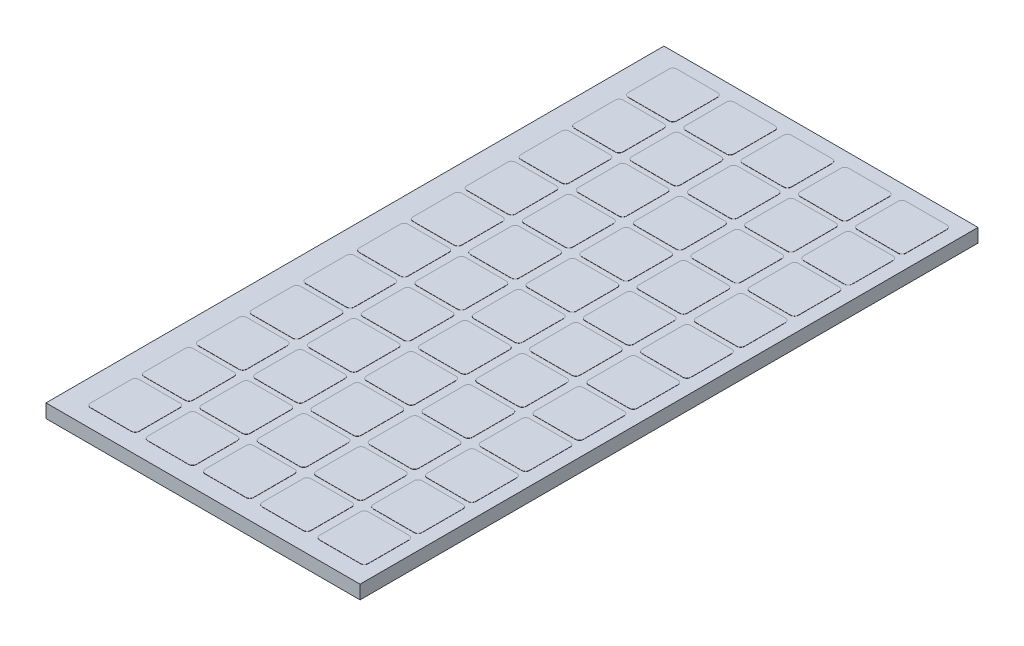
SolidWorks part; units mm, degrees
ref_plane "Спереди" through (0, 0, 0) normal (0, 0, 1) x (1, 0, 0)
ref_plane "Сверху" through (0, 0, 0) normal (0, 1, 0) x (1, 0, 0)
ref_plane "Справа" through (0, 0, 0) normal (1, 0, 0) x (0, 0, -1)
other "Центр тяжести"
other "Configuration Table"
sketch "Эскиз5" plane through (0, 0, 0) normal (0, 1, 0) x (1, 0, 0)
  line L0 (0, 0) -> (0, 1586)
  line L5 (0, 1586) -> (806, 1586)
  line L6 (806, 1586) -> (806, 0)
  line L7 (806, 0) -> (0, 0)
extrude "Бобышка-Вытянуть1" add sketch "Эскиз5" along normal blind 35
sketch "Эскиз7" plane through (0, 35, 0) normal (0, 1, 0) x (1, 0, 0)
  line L0 (806, 1586) -> (0, 1586) construction
  line L1 (761, 1551) -> (656, 1551)
  line L2 (771, 1541) -> (771, 1436)
  line L3 (761, 1426) -> (656, 1426)
  line L4 (646, 1541) -> (646, 1436)
  line L5 (806, 0) -> (806, 1586) construction
  line L6 (771, 1403) -> (771, 1298)
  line L7 (761, 1413) -> (656, 1413)
  line L8 (646, 1403) -> (646, 1298)
  line L9 (761, 1288) -> (656, 1288)
  line L10 (771, 1265) -> (771, 1160)
  line L11 (761, 1275) -> (656, 1275)
  line L12 (646, 1265) -> (646, 1160)
  line L13 (761, 1150) -> (656, 1150)
  line L14 (771, 1127) -> (771, 1022)
  line L15 (761, 1137) -> (656, 1137)
  line L16 (646, 1127) -> (646, 1022)
  line L17 (761, 1012) -> (656, 1012)
  line L18 (771, 989) -> (771, 884)
  line L19 (761, 999) -> (656, 999)
  line L20 (646, 989) -> (646, 884)
  line L21 (761, 874) -> (656, 874)
  line L22 (771, 851) -> (771, 746)
  line L23 (761, 861) -> (656, 861)
  line L24 (646, 851) -> (646, 746)
  line L25 (761, 736) -> (656, 736)
  line L26 (771, 713) -> (771, 608)
  line L27 (761, 723) -> (656, 723)
  line L28 (646, 713) -> (646, 608)
  line L29 (761, 598) -> (656, 598)
  line L30 (771, 575) -> (771, 470)
  line L31 (761, 585) -> (656, 585)
  line L32 (646, 575) -> (646, 470)
  line L33 (761, 460) -> (656, 460)
  line L34 (771, 437) -> (771, 332)
  line L35 (761, 447) -> (656, 447)
  line L36 (646, 437) -> (646, 332)
  line L37 (761, 322) -> (656, 322)
  line L38 (771, 299) -> (771, 194)
  line L39 (761, 309) -> (656, 309)
  line L40 (646, 299) -> (646, 194)
  line L41 (761, 184) -> (656, 184)
  line L42 (771, 161) -> (771, 56)
  line L43 (761, 171) -> (656, 171)
  line L44 (646, 161) -> (646, 56)
  line L45 (761, 46) -> (656, 46)
  line L46 (624, 1541) -> (624, 1436)
  line L47 (614, 1551) -> (509, 1551)
  line L48 (499, 1541) -> (499, 1436)
  line L49 (614, 1426) -> (509, 1426)
  line L50 (624, 1265) -> (624, 1160)
  line L51 (614, 1150) -> (509, 1150)
  line L52 (499, 1265) -> (499, 1160)
  line L53 (614, 1275) -> (509, 1275)
  line L54 (624, 1403) -> (624, 1298)
  line L55 (614, 1288) -> (509, 1288)
  line L56 (499, 1403) -> (499, 1298)
  line L57 (614, 1413) -> (509, 1413)
  line L58 (624, 989) -> (624, 884)
  line L59 (614, 874) -> (509, 874)
  line L60 (499, 989) -> (499, 884)
  line L61 (614, 999) -> (509, 999)
  line L62 (624, 1127) -> (624, 1022)
  line L63 (614, 1012) -> (509, 1012)
  line L64 (499, 1127) -> (499, 1022)
  line L65 (614, 1137) -> (509, 1137)
  line L66 (624, 851) -> (624, 746)
  line L67 (614, 736) -> (509, 736)
  line L68 (499, 851) -> (499, 746)
  line L69 (614, 861) -> (509, 861)
  line L70 (624, 713) -> (624, 608)
  line L71 (614, 598) -> (509, 598)
  line L72 (499, 713) -> (499, 608)
  line L73 (614, 723) -> (509, 723)
  line L74 (624, 575) -> (624, 470)
  line L75 (614, 460) -> (509, 460)
  line L76 (499, 575) -> (499, 470)
  line L77 (614, 585) -> (509, 585)
  line L78 (624, 437) -> (624, 332)
  line L79 (614, 322) -> (509, 322)
  line L80 (499, 437) -> (499, 332)
  line L81 (614, 447) -> (509, 447)
  line L82 (624, 299) -> (624, 194)
  line L83 (614, 184) -> (509, 184)
  line L84 (499, 299) -> (499, 194)
  line L85 (614, 309) -> (509, 309)
  line L86 (624, 161) -> (624, 56)
  line L87 (614, 46) -> (509, 46)
  line L88 (499, 161) -> (499, 56)
  line L89 (614, 171) -> (509, 171)
  line L90 (477, 1541) -> (477, 1436)
  line L91 (467, 1551) -> (362, 1551)
  line L92 (352, 1541) -> (352, 1436)
  line L93 (467, 1426) -> (362, 1426)
  line L94 (477, 1265) -> (477, 1160)
  line L95 (467, 1150) -> (362, 1150)
  line L96 (352, 1265) -> (352, 1160)
  line L97 (467, 1275) -> (362, 1275)
  line L98 (477, 1403) -> (477, 1298)
  line L99 (467, 1288) -> (362, 1288)
  line L100 (352, 1403) -> (352, 1298)
  line L101 (467, 1413) -> (362, 1413)
  line L102 (477, 989) -> (477, 884)
  line L103 (467, 874) -> (362, 874)
  line L104 (352, 989) -> (352, 884)
  line L105 (467, 999) -> (362, 999)
  line L106 (477, 1127) -> (477, 1022)
  line L107 (467, 1012) -> (362, 1012)
  line L108 (352, 1127) -> (352, 1022)
  line L109 (467, 1137) -> (362, 1137)
  line L110 (477, 851) -> (477, 746)
  line L111 (467, 736) -> (362, 736)
  line L112 (352, 851) -> (352, 746)
  line L113 (467, 861) -> (362, 861)
  line L114 (477, 713) -> (477, 608)
  line L115 (467, 598) -> (362, 598)
  line L116 (352, 713) -> (352, 608)
  line L117 (467, 723) -> (362, 723)
  line L118 (477, 575) -> (477, 470)
  line L119 (467, 460) -> (362, 460)
  line L120 (352, 575) -> (352, 470)
  line L121 (467, 585) -> (362, 585)
  line L122 (477, 437) -> (477, 332)
  line L123 (467, 322) -> (362, 322)
  line L124 (352, 437) -> (352, 332)
  line L125 (467, 447) -> (362, 447)
  line L126 (477, 299) -> (477, 194)
  line L127 (467, 184) -> (362, 184)
  line L128 (352, 299) -> (352, 194)
  line L129 (467, 309) -> (362, 309)
  line L130 (477, 161) -> (477, 56)
  line L131 (467, 46) -> (362, 46)
  line L132 (352, 161) -> (352, 56)
  line L133 (467, 171) -> (362, 171)
  line L134 (330, 1541) -> (330, 1436)
  line L135 (320, 1551) -> (215, 1551)
  line L136 (205, 1541) -> (205, 1436)
  line L137 (320, 1426) -> (215, 1426)
  line L138 (330, 1265) -> (330, 1160)
  line L139 (320, 1150) -> (215, 1150)
  line L140 (205, 1265) -> (205, 1160)
  line L141 (320, 1275) -> (215, 1275)
  line L142 (330, 1403) -> (330, 1298)
  line L143 (320, 1288) -> (215, 1288)
  line L144 (205, 1403) -> (205, 1298)
  line L145 (320, 1413) -> (215, 1413)
  line L146 (330, 989) -> (330, 884)
  line L147 (320, 874) -> (215, 874)
  line L148 (205, 989) -> (205, 884)
  line L149 (320, 999) -> (215, 999)
  line L150 (330, 1127) -> (330, 1022)
  line L151 (320, 1012) -> (215, 1012)
  line L152 (205, 1127) -> (205, 1022)
  line L153 (320, 1137) -> (215, 1137)
  line L154 (330, 851) -> (330, 746)
  line L155 (320, 736) -> (215, 736)
  line L156 (205, 851) -> (205, 746)
  line L157 (320, 861) -> (215, 861)
  line L158 (330, 713) -> (330, 608)
  line L159 (320, 598) -> (215, 598)
  line L160 (205, 713) -> (205, 608)
  line L161 (320, 723) -> (215, 723)
  line L162 (330, 575) -> (330, 470)
  line L163 (320, 460) -> (215, 460)
  line L164 (205, 575) -> (205, 470)
  line L165 (320, 585) -> (215, 585)
  line L166 (330, 437) -> (330, 332)
  line L167 (320, 322) -> (215, 322)
  line L168 (205, 437) -> (205, 332)
  line L169 (320, 447) -> (215, 447)
  line L170 (330, 299) -> (330, 194)
  line L171 (320, 184) -> (215, 184)
  line L172 (205, 299) -> (205, 194)
  line L173 (320, 309) -> (215, 309)
  line L174 (330, 161) -> (330, 56)
  line L175 (320, 46) -> (215, 46)
  line L176 (205, 161) -> (205, 56)
  line L177 (320, 171) -> (215, 171)
  line L178 (183, 1541) -> (183, 1436)
  line L179 (173, 1551) -> (68, 1551)
  line L180 (58, 1541) -> (58, 1436)
  line L181 (173, 1426) -> (68, 1426)
  line L182 (183, 1265) -> (183, 1160)
  line L183 (173, 1150) -> (68, 1150)
  line L184 (58, 1265) -> (58, 1160)
  line L185 (173, 1275) -> (68, 1275)
  line L186 (183, 1403) -> (183, 1298)
  line L187 (173, 1288) -> (68, 1288)
  line L188 (58, 1403) -> (58, 1298)
  line L189 (173, 1413) -> (68, 1413)
  line L190 (183, 989) -> (183, 884)
  line L191 (173, 874) -> (68, 874)
  line L192 (58, 989) -> (58, 884)
  line L193 (173, 999) -> (68, 999)
  line L194 (183, 1127) -> (183, 1022)
  line L195 (173, 1012) -> (68, 1012)
  line L196 (58, 1127) -> (58, 1022)
  line L197 (173, 1137) -> (68, 1137)
  line L198 (183, 851) -> (183, 746)
  line L199 (173, 736) -> (68, 736)
  line L200 (58, 851) -> (58, 746)
  line L201 (173, 861) -> (68, 861)
  line L202 (183, 713) -> (183, 608)
  line L203 (173, 598) -> (68, 598)
  line L204 (58, 713) -> (58, 608)
  line L205 (173, 723) -> (68, 723)
  line L206 (183, 575) -> (183, 470)
  line L207 (173, 460) -> (68, 460)
  line L208 (58, 575) -> (58, 470)
  line L209 (173, 585) -> (68, 585)
  line L210 (183, 437) -> (183, 332)
  line L211 (173, 322) -> (68, 322)
  line L212 (58, 437) -> (58, 332)
  line L213 (173, 447) -> (68, 447)
  line L214 (183, 299) -> (183, 194)
  line L215 (173, 184) -> (68, 184)
  line L216 (58, 299) -> (58, 194)
  line L217 (173, 309) -> (68, 309)
  line L218 (183, 161) -> (183, 56)
  line L219 (173, 46) -> (68, 46)
  line L220 (58, 161) -> (58, 56)
  line L221 (173, 171) -> (68, 171)
  arc A0 (173, 1426) -> (183, 1436) centre (173, 1436) ccw
  arc A1 (173, 1551) -> (183, 1541) centre (173, 1541) cw
  arc A2 (68, 1426) -> (58, 1436) centre (68, 1436) cw
  arc A3 (58, 1541) -> (68, 1551) centre (68, 1541) cw
  arc A4 (58, 161) -> (68, 171) centre (68, 161) cw
  arc A5 (183, 56) -> (173, 46) centre (173, 56) cw
  arc A6 (68, 46) -> (58, 56) centre (68, 56) cw
  arc A7 (183, 161) -> (173, 171) centre (173, 161) ccw
  arc A8 (58, 299) -> (68, 309) centre (68, 299) cw
  arc A9 (183, 194) -> (173, 184) centre (173, 194) cw
  arc A10 (68, 184) -> (58, 194) centre (68, 194) cw
  arc A11 (183, 299) -> (173, 309) centre (173, 299) ccw
  arc A12 (58, 437) -> (68, 447) centre (68, 437) cw
  arc A13 (183, 332) -> (173, 322) centre (173, 332) cw
  arc A14 (68, 322) -> (58, 332) centre (68, 332) cw
  arc A15 (183, 437) -> (173, 447) centre (173, 437) ccw
  arc A16 (58, 575) -> (68, 585) centre (68, 575) cw
  arc A17 (183, 470) -> (173, 460) centre (173, 470) cw
  arc A18 (68, 460) -> (58, 470) centre (68, 470) cw
  arc A19 (183, 575) -> (173, 585) centre (173, 575) ccw
  arc A20 (58, 713) -> (68, 723) centre (68, 713) cw
  arc A21 (183, 608) -> (173, 598) centre (173, 608) cw
  arc A22 (68, 598) -> (58, 608) centre (68, 608) cw
  arc A23 (183, 713) -> (173, 723) centre (173, 713) ccw
  arc A24 (58, 851) -> (68, 861) centre (68, 851) cw
  arc A25 (183, 746) -> (173, 736) centre (173, 746) cw
  arc A26 (68, 736) -> (58, 746) centre (68, 746) cw
  arc A27 (183, 851) -> (173, 861) centre (173, 851) ccw
  arc A28 (58, 989) -> (68, 999) centre (68, 989) cw
  arc A29 (183, 884) -> (173, 874) centre (173, 884) cw
  arc A30 (68, 874) -> (58, 884) centre (68, 884) cw
  arc A31 (183, 989) -> (173, 999) centre (173, 989) ccw
  arc A32 (58, 1127) -> (68, 1137) centre (68, 1127) cw
  arc A33 (183, 1022) -> (173, 1012) centre (173, 1022) cw
  arc A34 (68, 1012) -> (58, 1022) centre (68, 1022) cw
  arc A35 (183, 1127) -> (173, 1137) centre (173, 1127) ccw
  arc A36 (58, 1265) -> (68, 1275) centre (68, 1265) cw
  arc A37 (183, 1160) -> (173, 1150) centre (173, 1160) cw
  arc A38 (68, 1150) -> (58, 1160) centre (68, 1160) cw
  arc A39 (183, 1265) -> (173, 1275) centre (173, 1265) ccw
  arc A40 (58, 1403) -> (68, 1413) centre (68, 1403) cw
  arc A41 (183, 1298) -> (173, 1288) centre (173, 1298) cw
  arc A42 (68, 1288) -> (58, 1298) centre (68, 1298) cw
  arc A43 (183, 1403) -> (173, 1413) centre (173, 1403) ccw
  arc A44 (205, 161) -> (215, 171) centre (215, 161) cw
  arc A45 (330, 56) -> (320, 46) centre (320, 56) cw
  arc A46 (215, 46) -> (205, 56) centre (215, 56) cw
  arc A47 (330, 161) -> (320, 171) centre (320, 161) ccw
  arc A48 (205, 299) -> (215, 309) centre (215, 299) cw
  arc A49 (330, 194) -> (320, 184) centre (320, 194) cw
  arc A50 (215, 184) -> (205, 194) centre (215, 194) cw
  arc A51 (330, 299) -> (320, 309) centre (320, 299) ccw
  arc A52 (205, 437) -> (215, 447) centre (215, 437) cw
  arc A53 (330, 332) -> (320, 322) centre (320, 332) cw
  arc A54 (215, 322) -> (205, 332) centre (215, 332) cw
  arc A55 (330, 437) -> (320, 447) centre (320, 437) ccw
  arc A56 (205, 575) -> (215, 585) centre (215, 575) cw
  arc A57 (330, 470) -> (320, 460) centre (320, 470) cw
  arc A58 (215, 460) -> (205, 470) centre (215, 470) cw
  arc A59 (330, 575) -> (320, 585) centre (320, 575) ccw
  arc A60 (205, 713) -> (215, 723) centre (215, 713) cw
  arc A61 (330, 608) -> (320, 598) centre (320, 608) cw
  arc A62 (215, 598) -> (205, 608) centre (215, 608) cw
  arc A63 (330, 713) -> (320, 723) centre (320, 713) ccw
  arc A64 (205, 851) -> (215, 861) centre (215, 851) cw
  arc A65 (330, 746) -> (320, 736) centre (320, 746) cw
  arc A66 (215, 736) -> (205, 746) centre (215, 746) cw
  arc A67 (330, 851) -> (320, 861) centre (320, 851) ccw
  arc A68 (205, 989) -> (215, 999) centre (215, 989) cw
  arc A69 (330, 884) -> (320, 874) centre (320, 884) cw
  arc A70 (215, 874) -> (205, 884) centre (215, 884) cw
  arc A71 (330, 989) -> (320, 999) centre (320, 989) ccw
  arc A72 (205, 1127) -> (215, 1137) centre (215, 1127) cw
  arc A73 (330, 1022) -> (320, 1012) centre (320, 1022) cw
  arc A74 (215, 1012) -> (205, 1022) centre (215, 1022) cw
  arc A75 (330, 1127) -> (320, 1137) centre (320, 1127) ccw
  arc A76 (205, 1265) -> (215, 1275) centre (215, 1265) cw
  arc A77 (330, 1160) -> (320, 1150) centre (320, 1160) cw
  arc A78 (215, 1150) -> (205, 1160) centre (215, 1160) cw
  arc A79 (330, 1265) -> (320, 1275) centre (320, 1265) ccw
  arc A80 (205, 1403) -> (215, 1413) centre (215, 1403) cw
  arc A81 (330, 1298) -> (320, 1288) centre (320, 1298) cw
  arc A82 (215, 1288) -> (205, 1298) centre (215, 1298) cw
  arc A83 (330, 1403) -> (320, 1413) centre (320, 1403) ccw
  arc A84 (215, 1551) -> (205, 1541) centre (215, 1541) ccw
  arc A85 (330, 1436) -> (320, 1426) centre (320, 1436) cw
  arc A86 (205, 1436) -> (215, 1426) centre (215, 1436) ccw
  arc A87 (330, 1541) -> (320, 1551) centre (320, 1541) ccw
  arc A88 (352, 161) -> (362, 171) centre (362, 161) cw
  arc A89 (477, 56) -> (467, 46) centre (467, 56) cw
  arc A90 (362, 46) -> (352, 56) centre (362, 56) cw
  arc A91 (477, 161) -> (467, 171) centre (467, 161) ccw
  arc A92 (352, 299) -> (362, 309) centre (362, 299) cw
  arc A93 (477, 194) -> (467, 184) centre (467, 194) cw
  arc A94 (362, 184) -> (352, 194) centre (362, 194) cw
  arc A95 (477, 299) -> (467, 309) centre (467, 299) ccw
  arc A96 (352, 437) -> (362, 447) centre (362, 437) cw
  arc A97 (477, 332) -> (467, 322) centre (467, 332) cw
  arc A98 (362, 322) -> (352, 332) centre (362, 332) cw
  arc A99 (477, 437) -> (467, 447) centre (467, 437) ccw
  arc A100 (352, 575) -> (362, 585) centre (362, 575) cw
  arc A101 (477, 470) -> (467, 460) centre (467, 470) cw
  arc A102 (362, 460) -> (352, 470) centre (362, 470) cw
  arc A103 (477, 575) -> (467, 585) centre (467, 575) ccw
  arc A104 (352, 713) -> (362, 723) centre (362, 713) cw
  arc A105 (477, 608) -> (467, 598) centre (467, 608) cw
  arc A106 (362, 598) -> (352, 608) centre (362, 608) cw
  arc A107 (477, 713) -> (467, 723) centre (467, 713) ccw
  arc A108 (352, 851) -> (362, 861) centre (362, 851) cw
  arc A109 (477, 746) -> (467, 736) centre (467, 746) cw
  arc A110 (362, 736) -> (352, 746) centre (362, 746) cw
  arc A111 (477, 851) -> (467, 861) centre (467, 851) ccw
  arc A112 (352, 989) -> (362, 999) centre (362, 989) cw
  arc A113 (477, 884) -> (467, 874) centre (467, 884) cw
  arc A114 (362, 874) -> (352, 884) centre (362, 884) cw
  arc A115 (477, 989) -> (467, 999) centre (467, 989) ccw
  arc A116 (352, 1127) -> (362, 1137) centre (362, 1127) cw
  arc A117 (477, 1022) -> (467, 1012) centre (467, 1022) cw
  arc A118 (362, 1012) -> (352, 1022) centre (362, 1022) cw
  arc A119 (477, 1127) -> (467, 1137) centre (467, 1127) ccw
  arc A120 (352, 1265) -> (362, 1275) centre (362, 1265) cw
  arc A121 (477, 1160) -> (467, 1150) centre (467, 1160) cw
  arc A122 (362, 1150) -> (352, 1160) centre (362, 1160) cw
  arc A123 (477, 1265) -> (467, 1275) centre (467, 1265) ccw
  arc A124 (352, 1403) -> (362, 1413) centre (362, 1403) cw
  arc A125 (477, 1298) -> (467, 1288) centre (467, 1298) cw
  arc A126 (362, 1288) -> (352, 1298) centre (362, 1298) cw
  arc A127 (477, 1403) -> (467, 1413) centre (467, 1403) ccw
  arc A128 (362, 1551) -> (352, 1541) centre (362, 1541) ccw
  arc A129 (477, 1436) -> (467, 1426) centre (467, 1436) cw
  arc A130 (352, 1436) -> (362, 1426) centre (362, 1436) ccw
  arc A131 (477, 1541) -> (467, 1551) centre (467, 1541) ccw
  arc A132 (499, 161) -> (509, 171) centre (509, 161) cw
  arc A133 (624, 56) -> (614, 46) centre (614, 56) cw
  arc A134 (509, 46) -> (499, 56) centre (509, 56) cw
  arc A135 (624, 161) -> (614, 171) centre (614, 161) ccw
  arc A136 (499, 299) -> (509, 309) centre (509, 299) cw
  arc A137 (624, 194) -> (614, 184) centre (614, 194) cw
  arc A138 (509, 184) -> (499, 194) centre (509, 194) cw
  arc A139 (624, 299) -> (614, 309) centre (614, 299) ccw
  arc A140 (499, 437) -> (509, 447) centre (509, 437) cw
  arc A141 (624, 332) -> (614, 322) centre (614, 332) cw
  arc A142 (509, 322) -> (499, 332) centre (509, 332) cw
  arc A143 (624, 437) -> (614, 447) centre (614, 437) ccw
  arc A144 (499, 575) -> (509, 585) centre (509, 575) cw
  arc A145 (624, 470) -> (614, 460) centre (614, 470) cw
  arc A146 (509, 460) -> (499, 470) centre (509, 470) cw
  arc A147 (624, 575) -> (614, 585) centre (614, 575) ccw
  arc A148 (499, 713) -> (509, 723) centre (509, 713) cw
  arc A149 (624, 608) -> (614, 598) centre (614, 608) cw
  arc A150 (509, 598) -> (499, 608) centre (509, 608) cw
  arc A151 (624, 713) -> (614, 723) centre (614, 713) ccw
  arc A152 (499, 851) -> (509, 861) centre (509, 851) cw
  arc A153 (624, 746) -> (614, 736) centre (614, 746) cw
  arc A154 (509, 736) -> (499, 746) centre (509, 746) cw
  arc A155 (624, 851) -> (614, 861) centre (614, 851) ccw
  arc A156 (499, 989) -> (509, 999) centre (509, 989) cw
  arc A157 (624, 884) -> (614, 874) centre (614, 884) cw
  arc A158 (509, 874) -> (499, 884) centre (509, 884) cw
  arc A159 (624, 989) -> (614, 999) centre (614, 989) ccw
  arc A160 (499, 1127) -> (509, 1137) centre (509, 1127) cw
  arc A161 (624, 1022) -> (614, 1012) centre (614, 1022) cw
  arc A162 (509, 1012) -> (499, 1022) centre (509, 1022) cw
  arc A163 (624, 1127) -> (614, 1137) centre (614, 1127) ccw
  arc A164 (499, 1265) -> (509, 1275) centre (509, 1265) cw
  arc A165 (624, 1160) -> (614, 1150) centre (614, 1160) cw
  arc A166 (509, 1150) -> (499, 1160) centre (509, 1160) cw
  arc A167 (624, 1265) -> (614, 1275) centre (614, 1265) ccw
  arc A168 (499, 1403) -> (509, 1413) centre (509, 1403) cw
  arc A169 (624, 1298) -> (614, 1288) centre (614, 1298) cw
  arc A170 (509, 1288) -> (499, 1298) centre (509, 1298) cw
  arc A171 (624, 1403) -> (614, 1413) centre (614, 1403) ccw
  arc A172 (509, 1551) -> (499, 1541) centre (509, 1541) ccw
  arc A173 (624, 1436) -> (614, 1426) centre (614, 1436) cw
  arc A174 (499, 1436) -> (509, 1426) centre (509, 1436) ccw
  arc A175 (656, 171) -> (646, 161) centre (656, 161) ccw
  arc A176 (771, 56) -> (761, 46) centre (761, 56) cw
  arc A177 (646, 56) -> (656, 46) centre (656, 56) ccw
  arc A178 (771, 161) -> (761, 171) centre (761, 161) ccw
  arc A179 (656, 309) -> (646, 299) centre (656, 299) ccw
  arc A180 (771, 194) -> (761, 184) centre (761, 194) cw
  arc A181 (646, 194) -> (656, 184) centre (656, 194) ccw
  arc A182 (771, 299) -> (761, 309) centre (761, 299) ccw
  arc A183 (656, 447) -> (646, 437) centre (656, 437) ccw
  arc A184 (771, 332) -> (761, 322) centre (761, 332) cw
  arc A185 (646, 332) -> (656, 322) centre (656, 332) ccw
  arc A186 (771, 437) -> (761, 447) centre (761, 437) ccw
  arc A187 (656, 585) -> (646, 575) centre (656, 575) ccw
  arc A188 (771, 470) -> (761, 460) centre (761, 470) cw
  arc A189 (646, 470) -> (656, 460) centre (656, 470) ccw
  arc A190 (771, 575) -> (761, 585) centre (761, 575) ccw
  arc A191 (656, 723) -> (646, 713) centre (656, 713) ccw
  arc A192 (771, 608) -> (761, 598) centre (761, 608) cw
  arc A193 (646, 608) -> (656, 598) centre (656, 608) ccw
  arc A194 (771, 713) -> (761, 723) centre (761, 713) ccw
  arc A195 (656, 861) -> (646, 851) centre (656, 851) ccw
  arc A196 (771, 746) -> (761, 736) centre (761, 746) cw
  arc A197 (646, 746) -> (656, 736) centre (656, 746) ccw
  arc A198 (771, 851) -> (761, 861) centre (761, 851) ccw
  arc A199 (656, 999) -> (646, 989) centre (656, 989) ccw
  arc A200 (771, 884) -> (761, 874) centre (761, 884) cw
  arc A201 (646, 884) -> (656, 874) centre (656, 884) ccw
  arc A202 (771, 989) -> (761, 999) centre (761, 989) ccw
  arc A203 (656, 1137) -> (646, 1127) centre (656, 1127) ccw
  arc A204 (771, 1022) -> (761, 1012) centre (761, 1022) cw
  arc A205 (646, 1022) -> (656, 1012) centre (656, 1022) ccw
  arc A206 (771, 1127) -> (761, 1137) centre (761, 1127) ccw
  arc A207 (656, 1275) -> (646, 1265) centre (656, 1265) ccw
  arc A208 (771, 1160) -> (761, 1150) centre (761, 1160) cw
  arc A209 (646, 1160) -> (656, 1150) centre (656, 1160) ccw
  arc A210 (771, 1265) -> (761, 1275) centre (761, 1265) ccw
  arc A211 (656, 1413) -> (646, 1403) centre (656, 1403) ccw
  arc A212 (771, 1298) -> (761, 1288) centre (761, 1298) cw
  arc A213 (646, 1298) -> (656, 1288) centre (656, 1298) ccw
  arc A214 (771, 1403) -> (761, 1413) centre (761, 1403) ccw
  arc A215 (624, 1541) -> (614, 1551) centre (614, 1541) ccw
  arc A216 (656, 1551) -> (646, 1541) centre (656, 1541) ccw
  arc A217 (771, 1436) -> (761, 1426) centre (761, 1436) cw
  arc A218 (656, 1426) -> (646, 1436) centre (656, 1436) cw
  arc A219 (761, 1551) -> (771, 1541) centre (761, 1541) cw
  dimension "D7" = 10
  dimension "D1" = 35
  dimension "D2" = 35
  dimension "D3" = 125
  dimension "D4" = 125
  dimension "D5" = 11
  dimension "D6" = 5
extrude "Бобышка-Вытянуть2" add sketch "Эскиз7" along normal blind 0.5 separate body
sketch "Эскиз8" plane through (0, 0, 0) normal (0, -1, 0) x (1, 0, 0)
  line L0 (806, 0) -> (806, -1586) construction
  line L1 (388, -808) -> (418, -808)
  line L2 (388, -808) -> (388, -778)
  line L3 (388, -778) -> (418, -778)
  line L4 (418, -808) -> (418, -778)
  line L5 (388, -808) -> (418, -778) construction
  line L6 (388, -778) -> (418, -808) construction
  line L7 (806, -1586) -> (0, -1586) construction
  point P0 (403, -793)
  dimension "D1" = 30
  dimension "D2" = 30
  dimension "D3" = 388
  dimension "D4" = 793
extrude "Бобышка-Вытянуть3" add sketch "Эскиз8" along normal blind 30
sketch "Эскиз9" plane through (388, 0, 0) normal (-1, 0, 0) x (0, 0, 1)
  line L0 (-778, -30) -> (-778, 0) construction
  line L1 (-778, -30) -> (-808, -30) construction
  circle A0 centre (-793, -15) radius 12.5
  dimension "D2" = 25
  dimension "D1" = 15
  dimension "D3" = 15
extrude "Вырез-Вытянуть1" cut sketch "Эскиз9" against normal through all
ref_point "Точка4"
